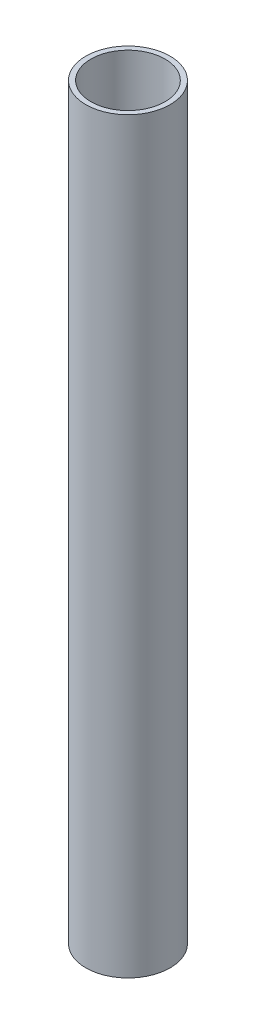
SolidWorks part; units mm, degrees
material "Thornel Mat VMA"
ref_plane "前视基准面" through (0, 0, 0) normal (0, 0, 1) x (1, 0, 0)
ref_plane "上视基准面" through (0, 0, 0) normal (0, 1, 0) x (1, 0, 0)
ref_plane "右视基准面" through (0, 0, 0) normal (1, 0, 0) x (0, 0, -1)
sketch "草图1" plane through (0, 0, 0) normal (0, 1, 0) x (1, 0, 0)
  circle A0 centre (0, 0) radius 12.5
  circle A1 centre (0, 0) radius 11
  dimension "D1" = 25
  dimension "D2" = 22
extrude "凸台-拉伸1" add sketch "草图1" along normal blind 222
